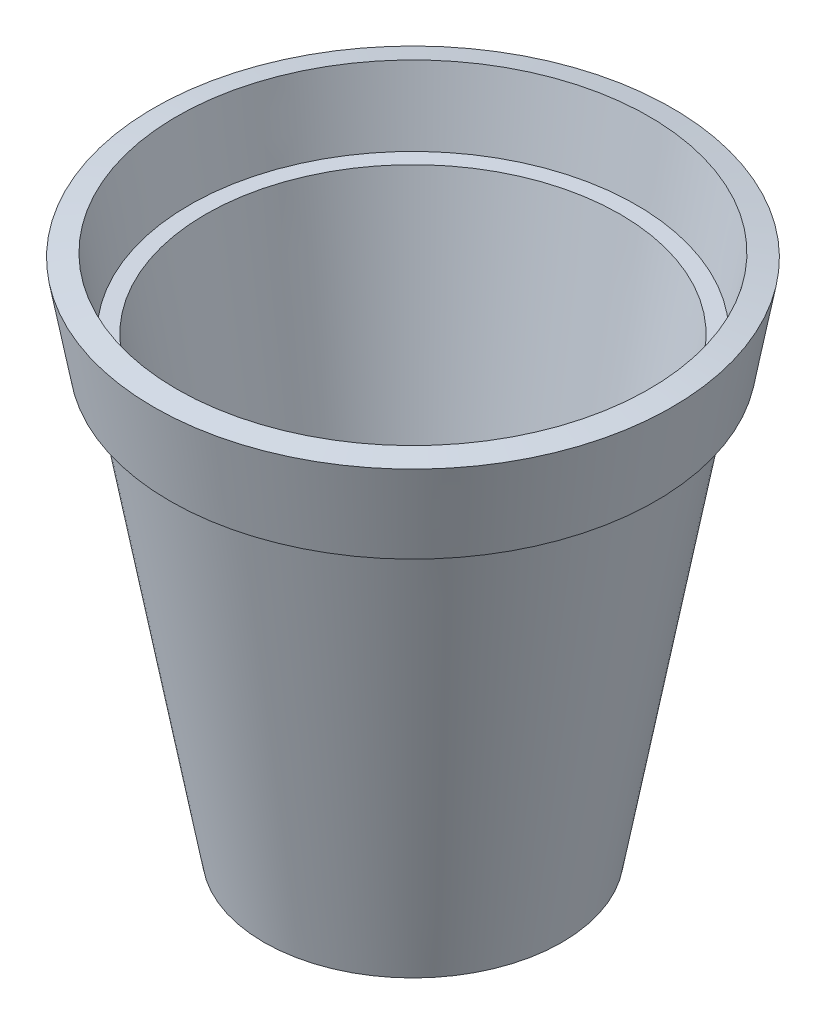
SolidWorks part; units mm, degrees
ref_plane "Front Plane" through (0, 0, 0) normal (0, 0, 1) x (1, 0, 0)
ref_plane "Top Plane" through (0, 0, 0) normal (0, 1, 0) x (1, 0, 0)
ref_plane "Right Plane" through (0, 0, 0) normal (1, 0, 0) x (0, 0, -1)
sketch "Sketch1" plane through (0, 0, 0) normal (0, 0, 1) x (1, 0, 0)
  line L0 (0, 0) -> (46, 0)
  line L1 (46, 0) -> (70, 132.48)
  line L2 (70, 132.48) -> (75, 132.48)
  line L3 (75, 132.48) -> (80, 160.08)
  line L4 (0, 7.2) -> (39.9872, 7.2)
  line L5 (39.9872, 7.2) -> (63.9872, 139.68)
  line L6 (63.9872, 139.68) -> (68.9872, 139.68)
  line L7 (68.9872, 139.68) -> (72.9153, 161.3635)
  line L8 (0, 7.2) -> (0, 0)
  line L9 (72.9153, 161.3635) -> (80, 160.08)
  dimension "D2" = 46
  dimension "D3" = 80
  dimension "D4" = 5
  dimension "D5" = 27.6
  dimension "D6" = 70
  dimension "D1" = 7.2
revolve "Revolve1" add sketch "Sketch1" angle 360 about L8
